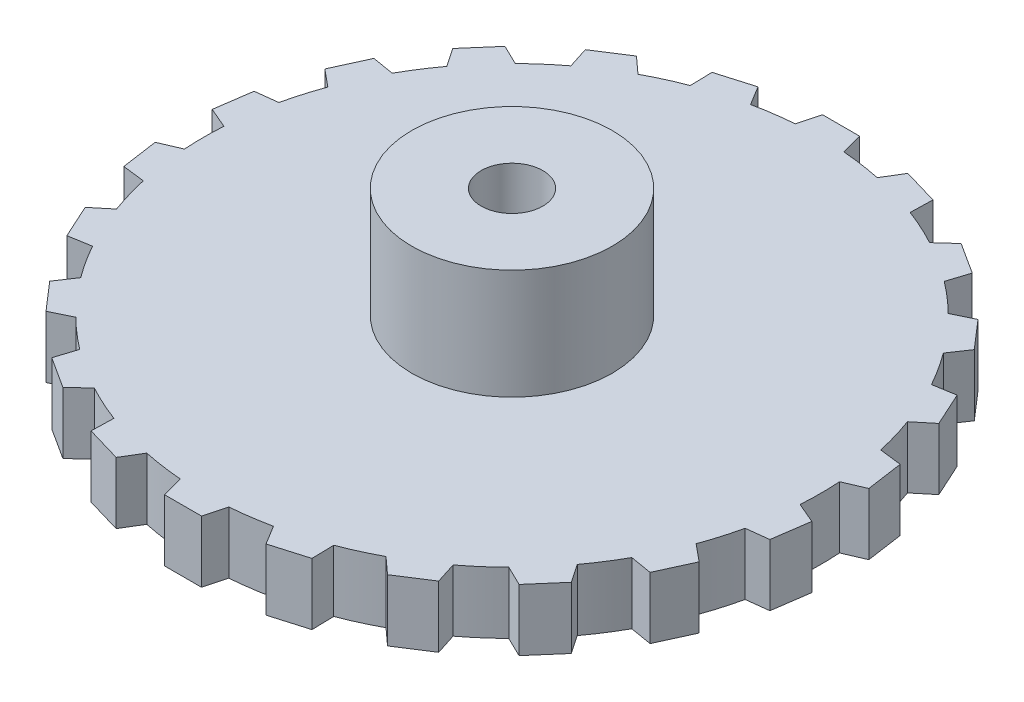
SolidWorks part; units mm, degrees
ref_plane "Front Plane" through (0, 0, 0) normal (0, 0, 1) x (1, 0, 0)
ref_plane "Top Plane" through (0, 0, 0) normal (0, 1, 0) x (1, 0, 0)
ref_plane "Right Plane" through (0, 0, 0) normal (1, 0, 0) x (0, 0, -1)
sketch "Sketch1" plane through (0, 0, 0) normal (0, 1, 0) x (1, 0, 0)
  circle A0 centre (0, 0) radius 30
  dimension "D1" = 60
extrude "Boss-Extrude3" add sketch "Sketch1" along normal blind 6
sketch "Sketch2" plane through (0, 6, 0) normal (0, 1, 0) x (1, 0, 0)
  line L0 (0, 0) -> (0, 62.0758) construction
  line L1 (0, 32) -> (1.8, 32)
  line L2 (1.8, 32) -> (3.4077, 26)
  line L3 (3.4077, 26) -> (0, 26)
  line L4 (0, 26) -> (-3.4077, 26)
  line L5 (-3.4077, 26) -> (-1.8, 32)
  line L6 (-1.8, 32) -> (0, 32)
  dimension "D1" = 1.8
  dimension "D2" = 1.8
  dimension "D3" = 75
  dimension "D4" = 75
  dimension "D5" = 32
extrude "Boss-Extrude2" add sketch "Sketch2" against normal blind 6
pattern_circular "CirPattern3" count 22 over 360 about axis through (0, 0, 0) along (0, 1, 0) of "Boss-Extrude2"
sketch "Sketch5" plane through (0, 6, 0) normal (0, 1, 0) x (1, 0, 0)
  circle A0 centre (0, 0) radius 9.75
  dimension "D1" = 19.5
extrude "Boss-Extrude4" add sketch "Sketch5" along normal blind 10.7
sketch "Sketch6" plane through (0, 16.7, 0) normal (0, 1, 0) x (1, 0, 0)
  circle A0 centre (0, 0) radius 3
  dimension "D1" = 6
extrude "Cut-Extrude1" cut sketch "Sketch6" against normal through all
